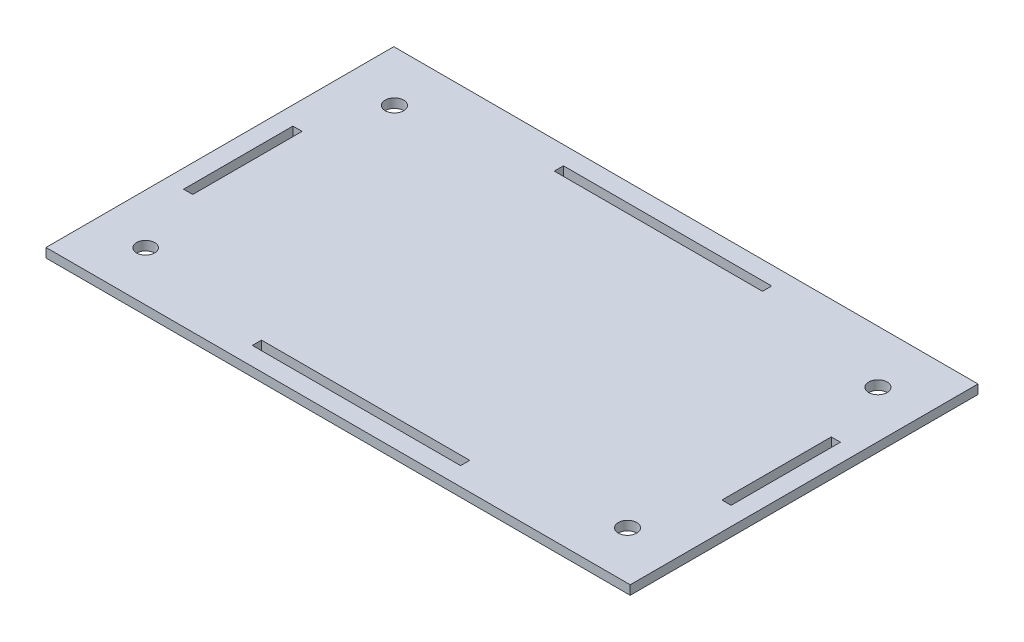
SolidWorks part; units mm, degrees
ref_plane "Front Plane" through (0, 0, 0) normal (0, 0, 1) x (1, 0, 0)
ref_plane "Top Plane" through (0, 0, 0) normal (0, 1, 0) x (1, 0, 0)
ref_plane "Right Plane" through (0, 0, 0) normal (1, 0, 0) x (0, 0, -1)
sketch "Sketch2" plane through (0, 0, 0) normal (0, 1, 0) x (1, 0, 0)
  line L9 (120.1865, -7.2219) -> (-7.2235, -7.2219)
  line L10 (120.1865, -7.2219) -> (120.1865, 68.6261)
  line L11 (120.1865, 68.6261) -> (-7.2235, 68.6261)
  line L12 (-7.2235, -7.2219) -> (-7.2235, 68.6261)
  line L15 (-5.2235, 66.6261) -> (118.1865, 66.6261) construction
  line L16 (-5.2235, 66.6261) -> (-5.2235, -5.2219) construction
  line L17 (-5.2235, -5.2219) -> (118.1865, -5.2219) construction
  line L18 (118.1865, 66.6261) -> (118.1865, -5.2219) construction
  line L19 (-1.2235, 42.6261) -> (-3.2235, 42.6261)
  line L20 (-1.2235, 42.6261) -> (-1.2235, 18.7781)
  line L21 (-1.2235, 18.7781) -> (-3.2235, 18.7781)
  line L22 (-3.2235, 42.6261) -> (-3.2235, 18.7781)
  line L23 (33.7765, 62.6261) -> (79.1865, 62.6261)
  line L24 (33.7765, 62.6261) -> (33.7765, 64.6261)
  line L25 (33.7765, 64.6261) -> (79.1865, 64.6261)
  line L26 (79.1865, 62.6261) -> (79.1865, 64.6261)
  line L27 (114.1865, 42.6261) -> (116.1865, 42.6261)
  line L28 (114.1865, 42.6261) -> (114.1865, 18.7781)
  line L29 (114.1865, 18.7781) -> (116.1865, 18.7781)
  line L30 (116.1865, 42.6261) -> (116.1865, 18.7781)
  line L31 (79.1865, -1.2219) -> (33.7765, -1.2219)
  line L32 (79.1865, -1.2219) -> (79.1865, -3.2219)
  line L33 (79.1865, -3.2219) -> (33.7765, -3.2219)
  line L34 (33.7765, -1.2219) -> (33.7765, -3.2219)
  circle A0 centre (3.7765, 3.7781) radius 1.3609 construction
  circle A1 centre (109.1865, 3.7781) radius 1.3609 construction
  circle A2 centre (3.7765, 57.6261) radius 1.6 construction
  circle A3 centre (109.1865, 57.6261) radius 1.3609 construction
  circle A7 centre (3.6953, 3.5852) radius 1.9754
  circle A10 centre (3.9452, 57.6066) radius 2.0206
  circle A11 centre (109.9031, 57.0856) radius 2.0058
  circle A12 centre (109.1405, 3.2382) radius 2.0076
  point P34 (33.7765, -2.2219)
  point P35 (115.1865, 42.6261)
  dimension "D20" = 2
  dimension "D2" = 2
  dimension "D3" = 15
  dimension "D4" = 15
  dimension "D5" = 30
  dimension "D6" = 30
  dimension "D7" = 30
  dimension "D8" = 30
  dimension "D9" = 15
  dimension "D10" = 15
  dimension "D11" = 5
  dimension "D12" = 2
  dimension "D13" = 5
  dimension "D14" = 5
  dimension "D15" = 5
  dimension "D16" = 9
  dimension "D17" = 9
  dimension "D18" = 9
  dimension "D19" = 9
  dimension "D21" = 2
  dimension "D22" = 2
extrude "Boss-Extrude1" add sketch "Sketch2" along normal blind 2
